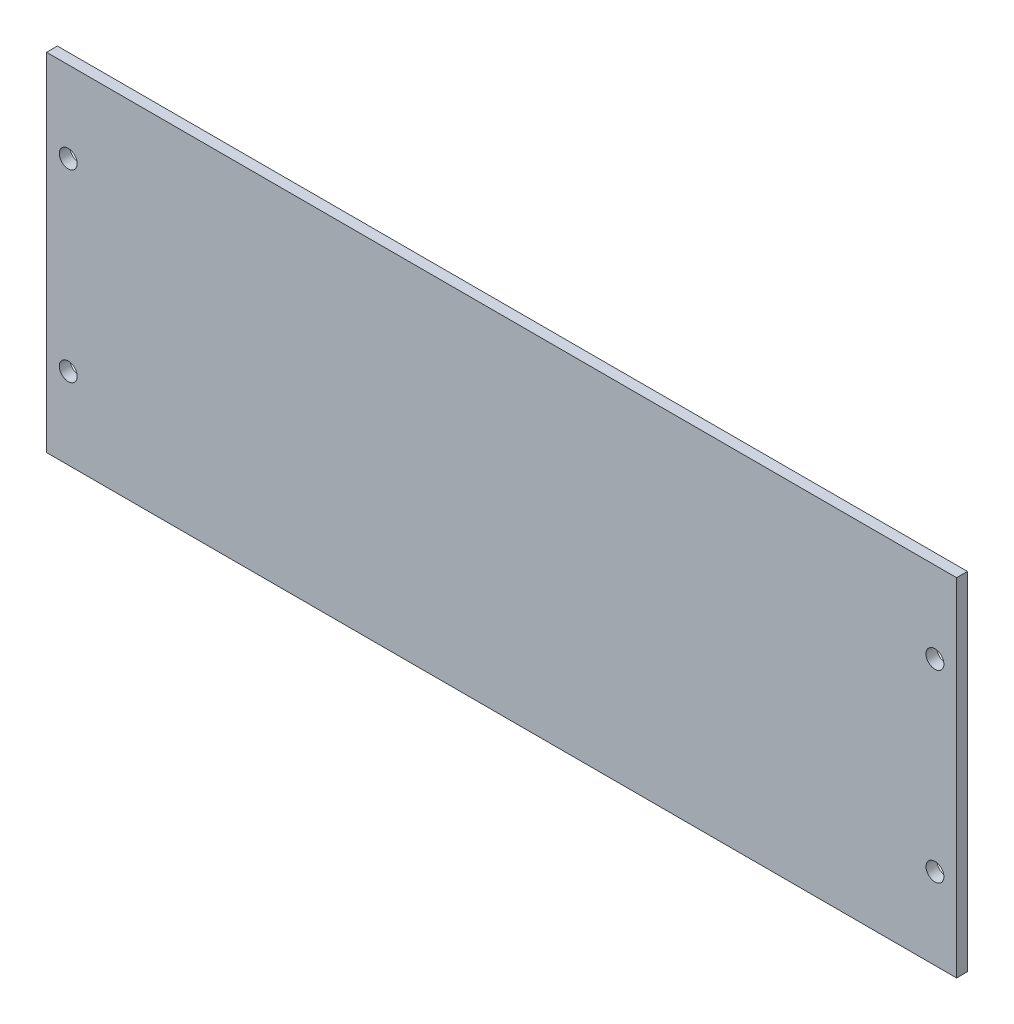
SolidWorks part; units mm, degrees
ref_plane "Plan de face" through (0, 0, 0) normal (0, 0, 1) x (1, 0, 0)
ref_plane "Plan de dessus" through (0, 0, 0) normal (0, 1, 0) x (1, 0, 0)
ref_plane "Plan de droite" through (0, 0, 0) normal (1, 0, 0) x (0, 0, -1)
sketch "Esquisse1" plane through (0, 0, 0) normal (0, 0, 1) x (1, 0, 0)
  line L1 (-168, -64) -> (168, -64)
  line L2 (-168, -64) -> (-168, 64)
  line L3 (-168, 64) -> (168, 64)
  line L4 (168, -64) -> (168, 64)
  line L5 (-168, -64) -> (168, 64) construction
  line L6 (-168, 64) -> (168, -64) construction
  point P0 (0, 0)
  dimension "D1" = 128
  dimension "D2" = 336
extrude "Boss.-Extru.1" add sketch "Esquisse1" along normal blind 4
sketch "Esquisse2" plane through (0, 0, 0) normal (0, 0, -1) x (-1, 0, 0)
  line L0 (168, -64) -> (-168, -64) construction
  line L1 (160, -56) -> (-160, -56) construction
  line L2 (160, -56) -> (160, 56) construction
  line L3 (160, 56) -> (-160, 56) construction
  line L4 (-160, -56) -> (-160, 56) construction
  line L5 (160, -56) -> (-160, 56) construction
  line L6 (160, 56) -> (-160, -56) construction
  line L7 (-168, -64) -> (-168, 64) construction
  line L8 (-153.9304, 0) -> (204.6118, 0) construction
  line L9 (0, -141.2759) -> (0, 199.6584) construction
  point P0 (0, 0)
  point P14 (-160, -34)
  point P15 (-160, 34)
  point P16 (160, -34)
  point P17 (160, 34)
  point P18 (0, 56)
  dimension "D1" = 8
  dimension "D2" = 8
  dimension "D3" = 30
hole_wizard "Dégagement M61" positions "Esquisse3D1" profile "Esquisse3" hole size "M6" standard "ISO" end condition through all
sketch3d "Esquisse3D1"
  point P3 (-160, 34, 0)
  point P6 (-160, -34, 0)
  point P9 (160, -34, 0)
  point P12 (160, 34, 0)
sketch "Esquisse3" plane through (-160, 34, 0) normal (1, 0, 0) x (0, 1, 0)
  line L0 (0, 0) -> (0, 4)
  line L1 (0, 4) -> (3.3, 4)
  line L2 (3.3, 4) -> (3.3, 0)
  line L5 (3.3, 0) -> (0, 0)
  line L11 (0, -6.35) -> (0, 107.95) construction
  dimension "Diamètre du perçage jusqu'au prochain" = 6.6
  dimension "Profondeur du perçage jusqu'au prochain" = 4
